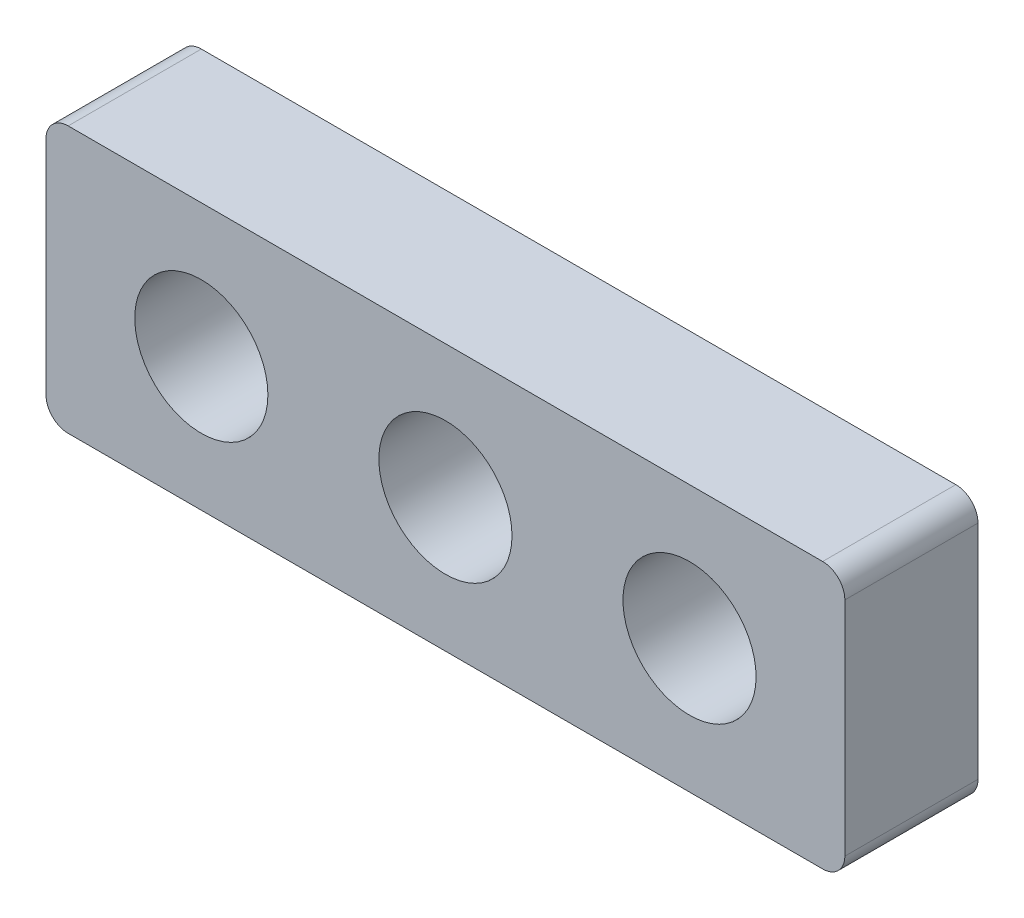
SolidWorks part; units mm, degrees
ref_plane "Front" through (0, 0, 0) normal (0, 0, 1) x (1, 0, 0)
ref_plane "Top" through (0, 0, 0) normal (0, 1, 0) x (1, 0, 0)
ref_plane "Right" through (0, 0, 0) normal (1, 0, 0) x (0, 0, -1)
sketch "草图1" plane through (0, 0, 0) normal (0, 0, 1) x (1, 0, 0)
  line L1 (9, -3) -> (-9, -3)
  line L2 (9, -3) -> (9, 3)
  line L3 (9, 3) -> (-9, 3)
  line L4 (-9, -3) -> (-9, 3)
  line L5 (9, -3) -> (-9, 3) construction
  line L6 (9, 3) -> (-9, -3) construction
  circle A0 centre (0, 0) radius 1.5
  point P0 (0, 0)
  dimension "D3" = 3
  dimension "D1" = 18
  dimension "D2" = 6
extrude "凸台-拉伸1" add sketch "草图1" along normal mid plane 3
sketch "草图2" plane through (0, 0, 1.5) normal (0, 0, 1) x (1, 0, 0)
  line L0 (-5.5, 0) -> (5.5, 0) construction
  circle A0 centre (-5.5, 0) radius 1.5
  circle A1 centre (5.5, 0) radius 1.5
  dimension "D1" = 3
  dimension "D2" = 3
  dimension "D3" = 11
extrude "切除-拉伸1" cut sketch "草图2" against normal through all
fillet "圆角1" radius 0.5 4 edges at (9, 3, 0) (9, -3, 0) (-9, -3, 0) (-9, 3, 0)
chamfer "倒角1" [suppressed] distance 0.2 angle 45
